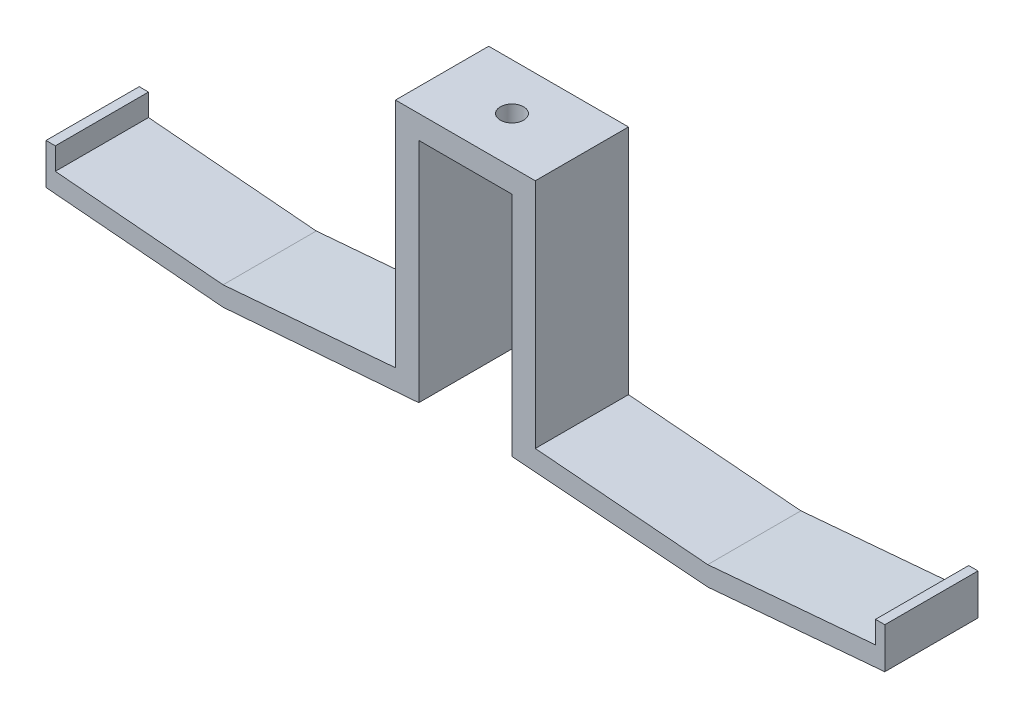
SolidWorks part; units mm, degrees
material "Nylon 6/10"
ref_plane "Front Plane" through (0, 0, 0) normal (0, 0, 1) x (1, 0, 0)
ref_plane "Top Plane" through (0, 0, 0) normal (0, 1, 0) x (1, 0, 0)
ref_plane "Right Plane" through (0, 0, 0) normal (1, 0, 0) x (0, 0, -1)
sketch "Sketch2" plane through (0, 0, 0) normal (0, 0, 1) x (1, 0, 0)
  line L1 (12.7, 0) -> (12.7, -61.918)
  line L2 (12.7, -61.918) -> (66.04, -66.0514)
  line L3 (66.04, -66.0514) -> (114.3, -61.918)
  line L4 (114.3, -61.918) -> (114.3, -50.8114)
  line L5 (111.76, -50.8114) -> (111.76, -56.838)
  line L6 (111.76, -56.838) -> (66.04, -60.7538)
  line L19 (114.3, -50.8114) -> (111.76, -50.8114)
  line L20 (0, 125.2351) -> (0, -75.9356) construction
  line L21 (12.7, 0) -> (-12.7, 0)
  line L22 (0, 0) -> (0, 6.35)
  line L23 (19.05, 6.35) -> (-19.05, 6.35)
  line L24 (19.05, 6.35) -> (19.05, 0)
  line L25 (19.05, 0) -> (19.05, -56.838)
  line L26 (19.05, -56.838) -> (66.04, -60.7538)
  line L27 (-19.05, 0) -> (-19.05, -56.838)
  line L28 (-19.05, 6.35) -> (-19.05, 0)
  line L29 (-12.7, 0) -> (-12.7, -61.918)
  line L30 (-12.7, -61.918) -> (-66.04, -66.0514)
  line L31 (-66.04, -66.0514) -> (-114.3, -61.918)
  line L32 (-114.3, -61.918) -> (-114.3, -50.8114)
  line L33 (-114.3, -50.8114) -> (-111.76, -50.8114)
  line L34 (-111.76, -50.8114) -> (-111.76, -56.838)
  line L35 (-111.76, -56.838) -> (-66.04, -60.7538)
  line L36 (-19.05, -56.838) -> (-66.04, -60.7538)
  dimension "D1" = 19.05
  dimension "D2" = 12.7
  dimension "D3" = 56.838
  dimension "D4" = 3.9158
  dimension "D5" = 61.918
  dimension "D6" = 2.54
  dimension "D7" = 45.72
  dimension "D8" = 46.99
  dimension "D9" = 15.24
  dimension "D10" = 6.35
extrude "Boss-Extrude1" add sketch "Sketch2" along normal blind 25.4 contours L26 L25 L24 L23 L22 L21 L1 L2 L3 L4 L19 L5 L6 | L27 L36 L35 L34 L33 L32 L31 L30 L29 L21 L22 L23 L28
sketch "Sketch3" plane through (0, 6.35, 0) normal (0, 1, 0) x (1, 0, 0)
  line L0 (19.05, -12.7) -> (-19.05, -12.7) construction
  line L1 (19.05, -25.4) -> (19.05, 0) construction
  line L2 (-19.05, -25.4) -> (-19.05, 0) construction
  circle A0 centre (0, -12.7) radius 3.175
  dimension "D1" = 6.35
extrude "Cut-Extrude1" cut sketch "Sketch3" against normal up to next
